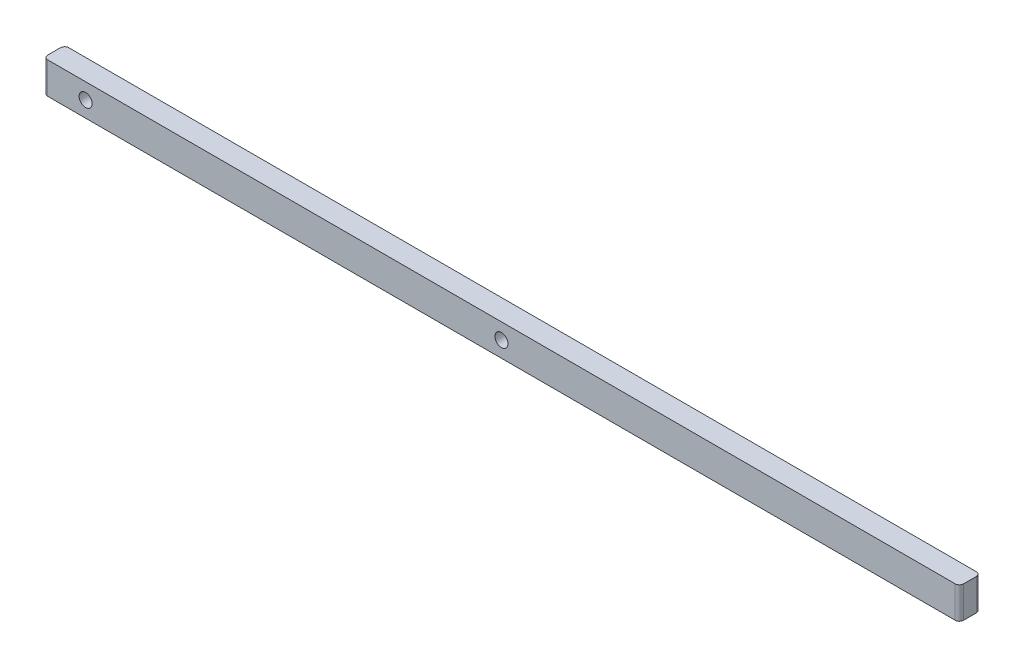
SolidWorks part; units mm, degrees
material "Balsa"
ref_plane "Front Plane" through (0, 0, 0) normal (0, 0, 1) x (1, 0, 0)
ref_plane "Top Plane" through (0, 0, 0) normal (0, 1, 0) x (1, 0, 0)
ref_plane "Right Plane" through (0, 0, 0) normal (1, 0, 0) x (0, 0, -1)
sketch "Sketch1" plane through (0, 0, 0) normal (0, 0, 1) x (1, 0, 0)
  line L1 (-276.225, -9.525) -> (276.225, -9.525)
  line L2 (-276.225, -9.525) -> (-276.225, 9.525)
  line L3 (-276.225, 9.525) -> (276.225, 9.525)
  line L4 (276.225, -9.525) -> (276.225, 9.525)
  line L5 (-276.225, -9.525) -> (276.225, 9.525) construction
  line L6 (-276.225, 9.525) -> (276.225, -9.525) construction
  point P0 (0, 0)
  dimension "D1" = 552.45
  dimension "D2" = 19.05
extrude "Boss-Extrude1" add sketch "Sketch1" along normal mid plane 12.7
sketch "Sketch2" plane through (0, 0, 6.35) normal (0, 0, 1) x (1, 0, 0)
  line L4 (276.225, -9.525) -> (276.225, 9.525)
  line L5 (276.225, 9.525) -> (-276.225, 9.525)
  line L6 (-276.225, 9.525) -> (-276.225, -9.525)
  line L7 (-276.225, -9.525) -> (276.225, -9.525)
  line L8 (276.225, -9.525) -> (276.225, 9.525)
  line L9 (276.225, 9.525) -> (-276.225, 9.525)
  line L10 (-276.225, 9.525) -> (-276.225, -9.525)
  line L11 (-276.225, -9.525) -> (276.225, -9.525)
  circle A0 centre (0, 0) radius 3.937
  circle A2 centre (-250.825, 0) radius 3.937
  point P11 (0, 0)
  point P12 (0, 0)
  point P13 (0, 0)
  dimension "D2" = 7.874
  dimension "D3" = 250.825
  dimension "D6" = 9.525
  dimension "D1" = 0
extrude "Cut-Extrude1" cut sketch "Sketch2" against normal through all both and the other way through all
fillet "Fillet1" radius 2.54 4 edges at (-276.225, 0, -6.35) (-276.225, 0, 6.35) (276.225, 0, -6.35) (276.225, 0, 6.35)
